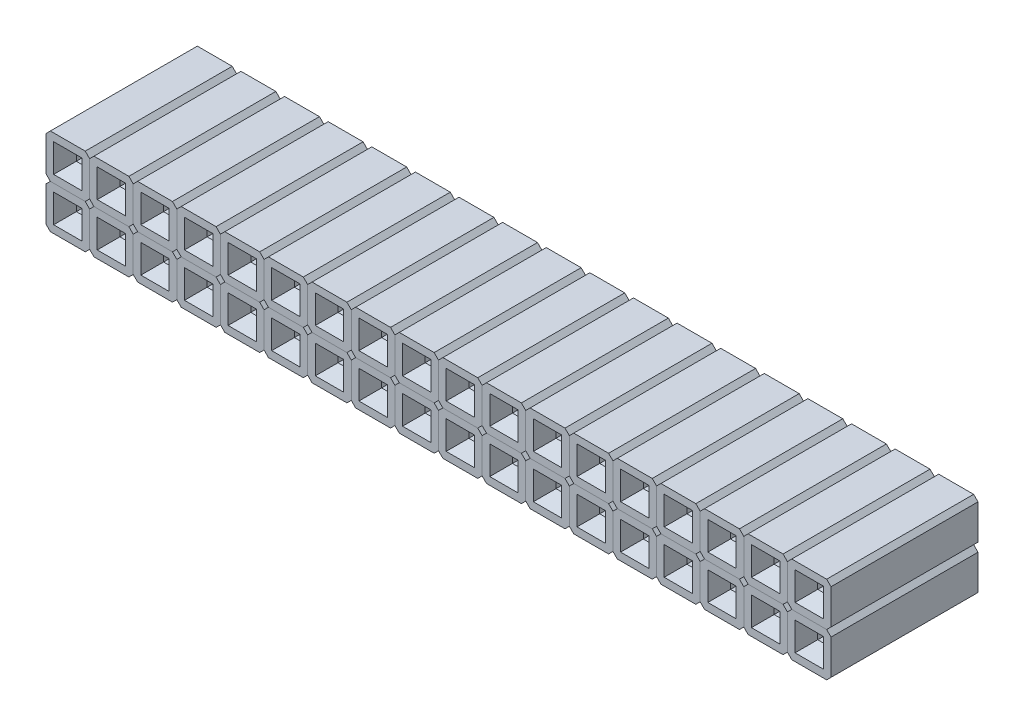
SolidWorks part; units mm, degrees
ref_plane "Front Plane" through (0, 0, 0) normal (0, 0, 1) x (1, 0, 0)
ref_plane "Top Plane" through (0, 0, 0) normal (0, 1, 0) x (1, 0, 0)
ref_plane "Right Plane" through (0, 0, 0) normal (1, 0, 0) x (0, 0, -1)
sketch "Sketch1" plane through (0, 0, 0) normal (0, 0, 1) x (1, 0, 0)
  line L1 (0, 0) -> (2.54, 0)
  line L2 (0, 0) -> (0, 2.54)
  line L3 (0, 2.54) -> (2.54, 2.54)
  line L4 (2.54, 0) -> (2.54, 2.54)
  dimension "D1" = 2.54
  dimension "D2" = 2.54
extrude "Boss-Extrude1" add sketch "Sketch1" along normal blind 8.5598
sketch "Sketch2" plane through (0, 0, 8.5598) normal (0, 0, 1) x (1, 0, 0)
  line L0 (0, 1.27) -> (2.54, 1.27) construction
  line L1 (0, 2.54) -> (0, 0) construction
  line L2 (2.54, 0) -> (2.54, 2.54) construction
  line L4 (0.9525, 0.9525) -> (1.5875, 0.9525)
  line L5 (0.9525, 0.9525) -> (0.9525, 1.5875)
  line L6 (0.9525, 1.5875) -> (1.5875, 1.5875)
  line L7 (1.5875, 0.9525) -> (1.5875, 1.5875)
  line L8 (0.9525, 0.9525) -> (1.5875, 1.5875) construction
  line L9 (0.9525, 1.5875) -> (1.5875, 0.9525) construction
  point P6 (1.27, 1.27)
  dimension "D1" = 0.635
extrude "Cut-Extrude1" cut sketch "Sketch2" against normal blind 6.35
chamfer "Chamfer1" distance 0.508 angle 58 4 edges at (0.9525, 1.27, 8.5598) (1.27, 0.9525, 8.5598) (1.5875, 1.27, 8.5598) (1.27, 1.5875, 8.5598)
chamfer "Chamfer2" distance 0.254 angle 45 4 edges at (0, 2.54, 4.2799) (2.54, 2.54, 4.2799) (2.54, 0, 4.2799) (0, 0, 4.2799)
pattern_linear "LPattern1" count 18 spacing 2.54 along (-1, 0, 0) count 2 spacing 2.54 along (0, 1, 0) of bodies 102
